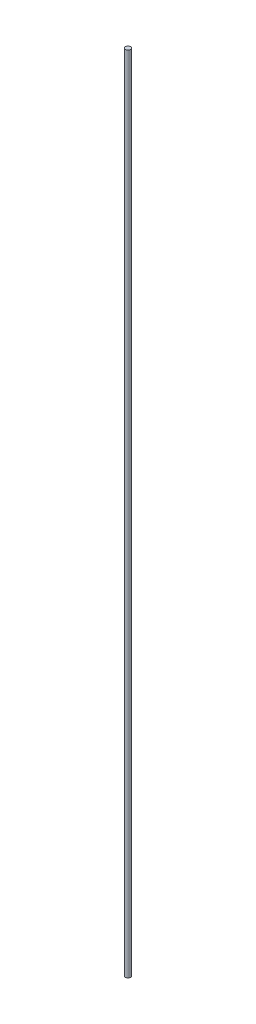
SolidWorks part; units mm, degrees
material "1060 Alloy"
ref_plane "Front Plane" through (0, 0, 0) normal (0, 0, 1) x (1, 0, 0)
ref_plane "Top Plane" through (0, 0, 0) normal (0, 1, 0) x (1, 0, 0)
ref_plane "Right Plane" through (0, 0, 0) normal (1, 0, 0) x (0, 0, -1)
sketch "Sketch1" plane through (0, 0, 0) normal (0, 1, 0) x (1, 0, 0)
  circle A0 centre (0, 0) radius 12.7
  dimension "D1" = 25.4
extrude "Boss-Extrude1" add sketch "Sketch1" along normal blind 3989.8227
equation "\"def\"= 0.009in"
equation "\"F\"= 450"
equation "\"d\"= 1in"
equation "\"E\"= 10000000"
equation "\"A\"= pi * ( ( \"d\" ^ 2 ) / 4 )"
equation "\"L\"= ( \"def\" * \"E\" * \"A\" ) / ( \"F\" )"
equation "\"D1@Boss-Extrude1\"=\"L\""
